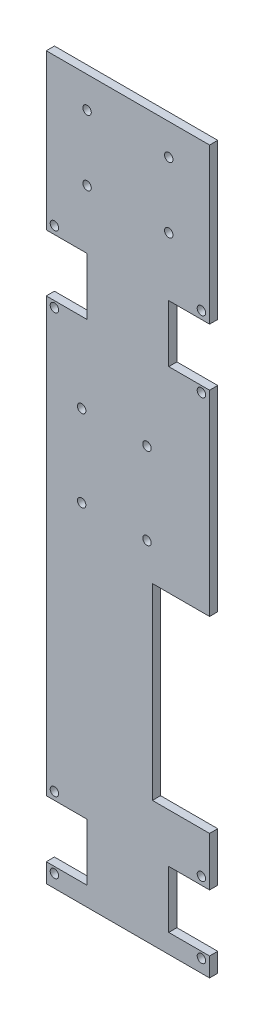
SolidWorks part; units mm, degrees
material "Thornel VCB-20 碳布"
ref_plane "前视基准面" through (0, 0, 0) normal (0, 0, 1) x (1, 0, 0)
ref_plane "上视基准面" through (0, 0, 0) normal (0, 1, 0) x (1, 0, 0)
ref_plane "右视基准面" through (0, 0, 0) normal (1, 0, 0) x (0, 0, -1)
other "Configuration Table"
sketch "草图1" plane through (0, 0, 0) normal (0, 0, 1) x (1, 0, 0)
  line L0 (0, 240) -> (0, 265)
  line L1 (0, 0) -> (60, 0)
  line L2 (0, 0) -> (0, 240)
  line L3 (0, 240) -> (60, 240) construction
  line L4 (60, 0) -> (60, 240)
  line L5 (0, 265) -> (60, 265)
  line L6 (60, 265) -> (60, 240)
  dimension "D1" = 60
  dimension "D2" = 240
  dimension "D3" = 25
extrude "凸台-拉伸1" add sketch "草图1" along normal blind 3
sketch "草图4" plane through (0, 0, 0) normal (0, 0, -1) x (-1, 0, 0)
  line L0 (-60, 7) -> (-45, 7)
  line L1 (-60, 0) -> (-60, 265) construction
  line L2 (-45, 7) -> (-45, 28)
  line L3 (-45, 28) -> (-60, 28)
  line L4 (0, 0) -> (-60, 0) construction
  line L5 (-60, 28) -> (-60, 7)
  line L6 (0, 265) -> (0, 0) construction
  line L7 (0, 28) -> (-15, 28)
  line L8 (0, 28) -> (0, 7)
  line L9 (0, 7) -> (-15, 7)
  line L10 (-15, 28) -> (-15, 7)
  line L11 (-60, 215) -> (0, 215) construction
  line L13 (0, 208) -> (-15, 208)
  line L14 (-15, 208) -> (-15, 187)
  line L15 (-15, 187) -> (0, 187)
  line L16 (-60, 208) -> (-45, 208)
  line L17 (-45, 208) -> (-45, 187)
  line L18 (-45, 187) -> (-60, 187)
  line L19 (-60, 187) -> (-60, 208)
  line L20 (0, 208) -> (0, 187)
  line L21 (-30, 0) -> (-30, 215) construction
  line L25 (-60, 265) -> (0, 265) construction
  dimension "D1" = 7
  dimension "D2" = 21
  dimension "D3" = 15
  dimension "D4" = 50
  dimension "D5" = 21
  dimension "D6" = 7
extrude "切除-拉伸1" cut sketch "草图4" against normal blind 3
sketch "草图5" plane through (0, 0, 0) normal (0, 0, -1) x (-1, 0, 0)
  circle A1 centre (-45, 229.6) radius 1.55
  circle A2 centre (-45, 229.6) radius 1.55
  circle A3 centre (-45, 253.6) radius 1.55
  circle A4 centre (-45, 253.6) radius 1.55
  circle A5 centre (-15, 253.6) radius 1.55
  circle A6 centre (-15, 253.6) radius 1.55
  circle A7 centre (-15, 229.6) radius 1.55
  circle A8 centre (-15, 229.6) radius 1.55
  circle A9 centre (-57, 184.75) radius 1.55
  circle A10 centre (-57, 184.75) radius 1.55
  circle A11 centre (-3, 184.75) radius 1.55
  circle A12 centre (-3, 184.75) radius 1.55
  circle A13 centre (-3, 210.85) radius 1.55
  circle A14 centre (-3, 210.85) radius 1.55
  circle A15 centre (-57, 210.85) radius 1.55
  circle A16 centre (-57, 210.85) radius 1.55
  circle A17 centre (-13, 127.7) radius 1.55
  circle A18 centre (-13, 127.7) radius 1.55
  circle A19 centre (-37, 127.7) radius 1.55
  circle A20 centre (-37, 127.7) radius 1.55
  circle A21 centre (-37, 157.7) radius 1.55
  circle A22 centre (-37, 157.7) radius 1.55
  circle A23 centre (-13, 157.7) radius 1.55
  circle A24 centre (-13, 157.7) radius 1.55
  circle A25 centre (-57, 4.75) radius 1.55
  circle A26 centre (-57, 4.75) radius 1.55
  circle A27 centre (-3, 4.75) radius 1.55
  circle A28 centre (-3, 4.75) radius 1.55
  circle A29 centre (-3, 30.85) radius 1.55
  circle A30 centre (-3, 30.85) radius 1.55
  circle A31 centre (-57, 30.85) radius 1.55
  circle A32 centre (-57, 30.85) radius 1.55
  dimension "D1" = 0
  dimension "D2" = 0
  dimension "D3" = 0
  dimension "D4" = 0
  dimension "D5" = 0
  dimension "D6" = 0
  dimension "D7" = 0
  dimension "D8" = 0
  dimension "D9" = 0
  dimension "D10" = 0
  dimension "D11" = 0
  dimension "D12" = 0
  dimension "D13" = 0
  dimension "D14" = 0
  dimension "D15" = 0
  dimension "D16" = 0
extrude "切除-拉伸2" cut sketch "草图5" against normal through all
sketch "草图7" plane through (0, 0, 0) normal (0, 0, -1) x (-1, 0, 0)
  line L0 (-60, 46) -> (-39, 46)
  line L1 (-60, 28) -> (-60, 187) construction
  line L2 (-39, 46) -> (-39, 115)
  line L3 (-39, 115) -> (-60, 115)
  line L4 (0, 0) -> (-60, 0) construction
  line L5 (-60, 46) -> (-60, 115)
  dimension "D1" = 46
  dimension "D2" = 115
  dimension "D3" = 21
extrude "切除-拉伸3" cut sketch "草图7" against normal through all
